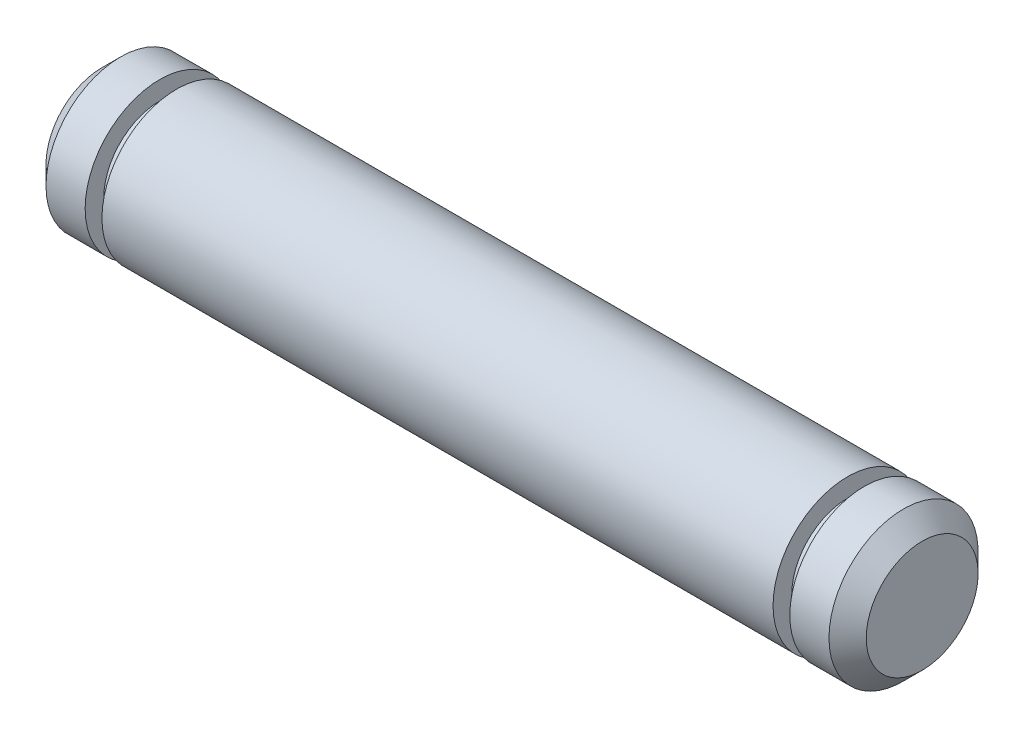
SolidWorks part; units mm, degrees
ref_plane "Front Plane" through (0, 0, 0) normal (0, 0, 1) x (1, 0, 0)
ref_plane "Top Plane" through (0, 0, 0) normal (0, 1, 0) x (1, 0, 0)
ref_plane "Right Plane" through (0, 0, 0) normal (1, 0, 0) x (0, 0, -1)
sketch "Sketch1" plane through (0, 0, 0) normal (0, 0, 1) x (1, 0, 0)
  line L0 (0, 0) -> (65.8791, 0) construction
  line L13 (0, 0) -> (0, 4)
  line L14 (0, 4) -> (3.1, 4)
  line L15 (3.1, 4) -> (3.1, 3)
  line L16 (3.1, 3) -> (4, 3)
  line L17 (4, 3) -> (4, 4)
  line L18 (4, 4) -> (40, 4)
  line L19 (40, 4) -> (40, 3)
  line L20 (40, 3) -> (40.9, 3)
  line L21 (40.9, 3) -> (40.9, 4)
  line L22 (40.9, 4) -> (44, 4)
  line L23 (44, 4) -> (44, 0)
  line L24 (44, 0) -> (0, 0)
  dimension "D1" = 8
  dimension "D2" = 6
  dimension "D3" = 6
  dimension "D4" = 44
  dimension "D5" = 36
  dimension "D6" = 0.9
  dimension "D7" = 0.9
  dimension "D8" = 4
revolve "Revolve1" add sketch "Sketch1" angle 360 about L0
chamfer "Chamfer1" distance 1 2 edges at (0, 0, 4) (44, 0, 4)
